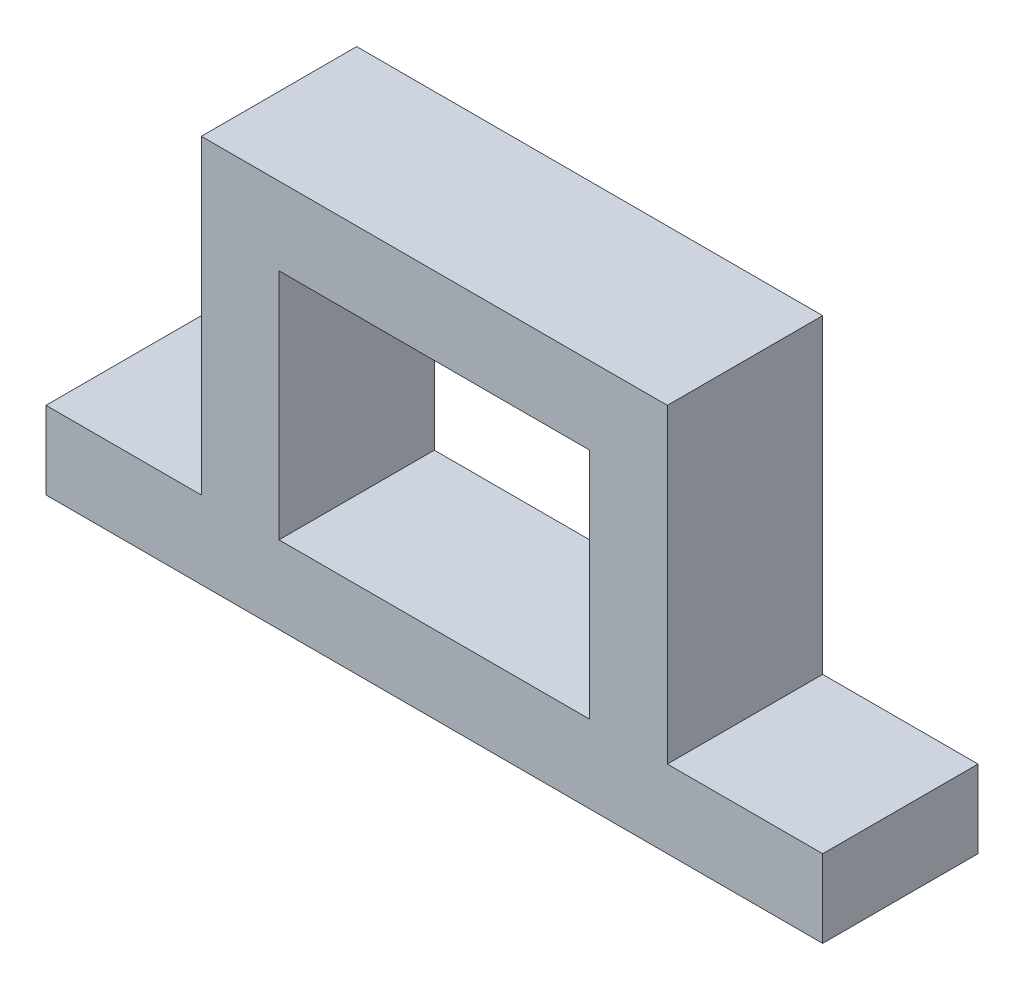
SolidWorks part; units mm, degrees
ref_plane "Front" through (0, 0, 0) normal (0, 0, 1) x (1, 0, 0)
ref_plane "Top" through (0, 0, 0) normal (0, 1, 0) x (1, 0, 0)
ref_plane "Right" through (0, 0, 0) normal (1, 0, 0) x (0, 0, -1)
sketch "Sketch1" plane through (0, 0, 0) normal (0, 0, 1) x (1, 0, 0)
  line L13 (0, 0) -> (30, 0)
  line L14 (0, 0) -> (0, 25)
  line L15 (0, 25) -> (30, 25)
  line L16 (30, 0) -> (30, 25)
  dimension "D1" = 30
  dimension "D2" = 25
extrude "Boss-Extrude1" add sketch "Sketch1" along normal blind 10 contours L15 L16 L13 L14
sketch "Sketch2" plane through (0, 0, 10) normal (0, 0, 1) x (1, 0, 0)
  line L0 (-10, 5) -> (40, 0) construction
  line L5 (-10, 0) -> (40, 0)
  line L6 (-10, 0) -> (-10, 5)
  line L7 (-10, 5) -> (40, 5)
  line L8 (40, 0) -> (40, 5)
  line L9 (40, 5) -> (-10, 0) construction
  line L10 (0, 25) -> (30, 25) construction
  line L11 (0, 0) -> (30, 0) construction
  point P4 (15, 2.5)
  point P7 (15, 25)
  dimension "D1" = 50
  dimension "D2" = 0
  dimension "D3" = 0
  dimension "D4" = 5
extrude "Boss-Extrude2" add sketch "Sketch2" against normal up to surface (10 mm away) up to face at (15, 12.5, 0)
sketch "Sketch3" plane through (0, 0, 10) normal (0, 0, 1) x (1, 0, 0)
  line L1 (5, 5) -> (25, 5)
  line L2 (5, 5) -> (5, 20)
  line L3 (5, 20) -> (25, 20)
  line L4 (25, 5) -> (25, 20)
  line L5 (0, 25) -> (30, 25) construction
  line L6 (0, 5) -> (0, 25) construction
  line L7 (30, 5) -> (30, 25) construction
  line L8 (0, 5) -> (-10, 5) construction
  dimension "D1" = 5
  dimension "D2" = 5
  dimension "D3" = 5
  dimension "D4" = 0
extrude "Cut-Extrude1" cut sketch "Sketch3" against normal through all both and the other way through all
ref_plane "Plane1" through (0, 0, 5) normal (0, 0, 1) x (1, 0, 0)
ref_plane "Plane2" through (15, 0, 0) normal (-1, 0, 0) x (0, 0, 1)
